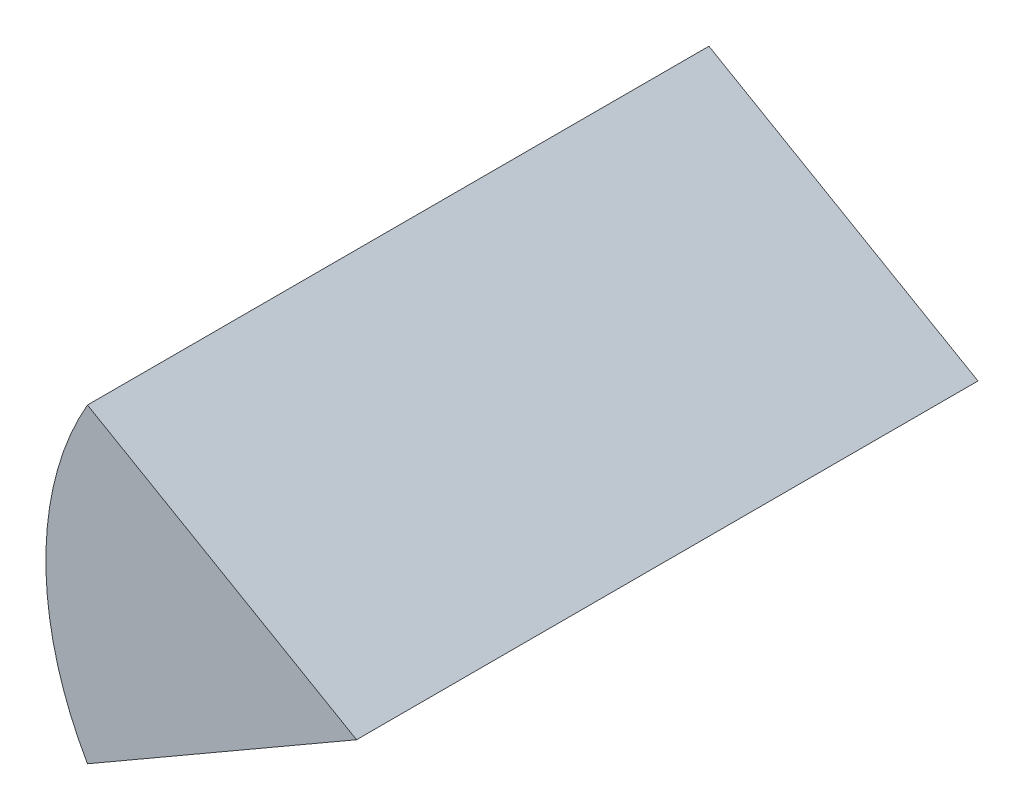
SolidWorks part; units mm, degrees
ref_plane "Alzado" through (0, 0, 0) normal (0, 0, 1) x (1, 0, 0)
ref_plane "Planta" through (0, 0, 0) normal (0, 1, 0) x (1, 0, 0)
ref_plane "Vista lateral" through (0, 0, 0) normal (1, 0, 0) x (0, 0, -1)
sketch "Croquis1" plane through (0, 0, 0) normal (0, 0, 1) x (1, 0, 0)
  line L1 (0, 0) -> (-21.6506, 12.5)
  line L2 (0, 0) -> (-21.6506, -12.5)
  arc A0 (-21.6506, 12.5) -> (-21.6506, -12.5) centre (0, 0) ccw
  dimension "D1" = 50
  dimension "D2" = 60
extrude "Saliente-Extruir1" add sketch "Croquis1" along normal blind 50
sketch "Croquis2" plane through (0, 0, 0) normal (0, 0, -1) x (-1, 0, 0)
  circle A0 centre (15.7715, 0) radius 5
  dimension "D1" = 10
extrude "Cortar-Extruir1" cut sketch "Croquis2" against normal blind 10
